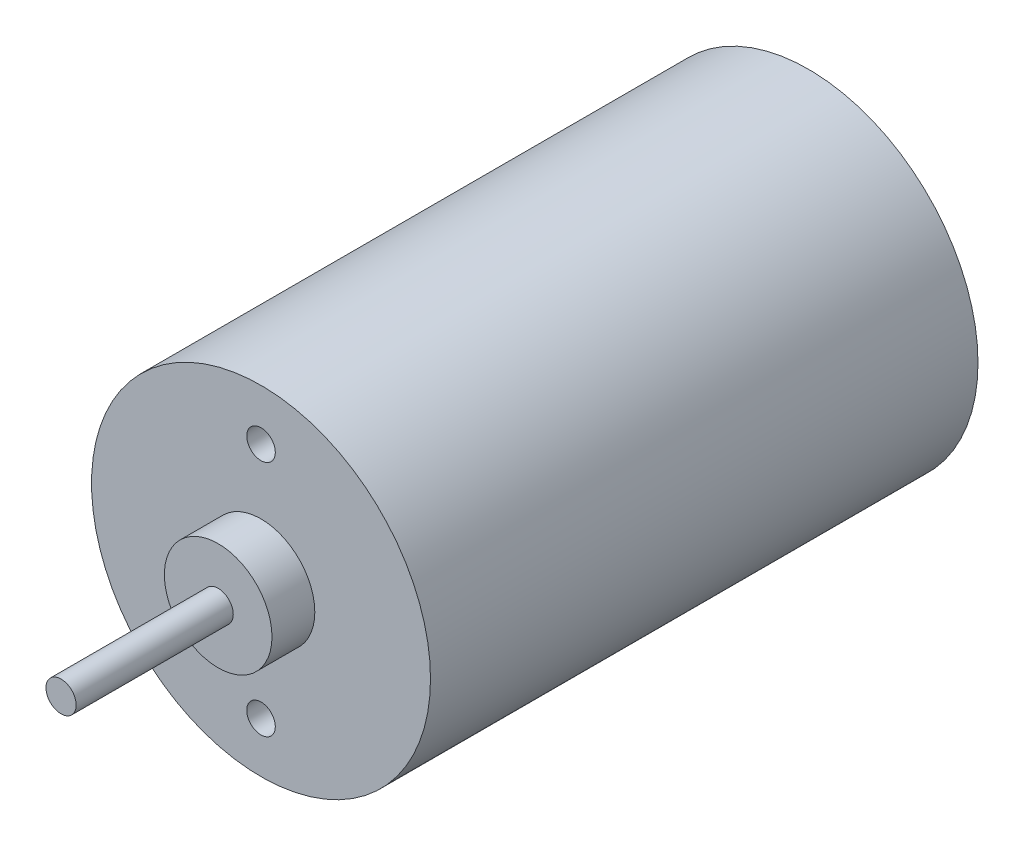
SolidWorks part; units mm, degrees
ref_plane "Front Plane" through (0, 0, 0) normal (0, 0, 1) x (1, 0, 0)
ref_plane "Top Plane" through (0, 0, 0) normal (0, 1, 0) x (1, 0, 0)
ref_plane "Right Plane" through (0, 0, 0) normal (1, 0, 0) x (0, 0, -1)
sketch "Sketch1" plane through (0, 0, 0) normal (0, 0, 1) x (1, 0, 0)
  circle A0 centre (0, 0) radius 17.8
  circle A3 centre (0, 12.446) radius 1.5 construction
  circle A4 centre (0, -12.5) radius 1.5 construction
  dimension "D1" = 35.6
  dimension "D4" = 3
  dimension "D5" = 3
  dimension "D2" = 12.5
extrude "Boss-Extrude1" add sketch "Sketch1" along normal blind 57.5
sketch "Sketch2" plane through (0, 0, 57.5) normal (0, 0, 1) x (1, 0, 0)
  circle A0 centre (0, 0) radius 5.65
  circle A1 centre (0, 12.446) radius 1.5 construction
  circle A2 centre (0, -12.5) radius 1.5 construction
  dimension "D1" = 11.3
extrude "Boss-Extrude2" add sketch "Sketch2" along normal blind 4.5
sketch "Sketch3" plane through (0, 0, 62) normal (0, 0, 1) x (1, 0, 0)
  circle A0 centre (0, 0) radius 1.585
  dimension "D1" = 3.17
extrude "Boss-Extrude3" add sketch "Sketch3" along normal blind 16.5
hole_wizard "Ø3.0 (3) Diameter Hole1" positions "Sketch7" profile "Sketch8" hole size "Ø3.0" standard "ANSI Metric"
sketch "Sketch7" plane through (0, 0, 57.5) normal (0, 0, 1) x (1, 0, 0)
  point P0 (0, 12.446)
  point P3 (0, -12.5)
sketch "Sketch8" plane through (0, 12.446, 57.5) normal (1, 0, 0) x (0, -1, 0)
  line L0 (0, 0) -> (0, 7.2513)
  line L1 (0, 7.2513) -> (1.5, 6.35)
  line L2 (1.5, 6.35) -> (1.5, 0)
  line L5 (1.5, 0) -> (0, 0)
  line L10 (0, 7.2513) -> (-1.5, 6.35) construction
  line L11 (0, -6.35) -> (0, 107.95) construction
  dimension "Hole Dia." = 3
  dimension "Hole Depth" = 6.35
  dimension "Drill Angle" = 118
